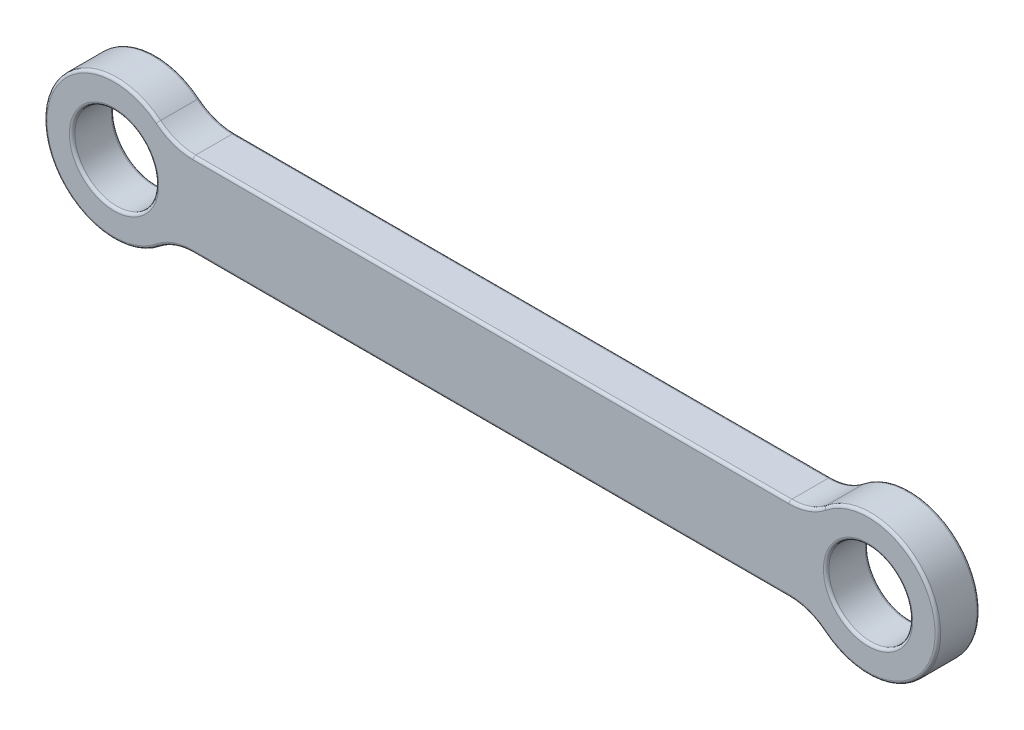
SolidWorks part; units mm, degrees
ref_plane "Front Plane" through (0, 0, 0) normal (0, 0, 1) x (1, 0, 0)
ref_plane "Top Plane" through (0, 0, 0) normal (0, 1, 0) x (1, 0, 0)
ref_plane "Right Plane" through (0, 0, 0) normal (1, 0, 0) x (0, 0, -1)
sketch "Sketch2" plane through (0, 0, 0) normal (0, 0, 1) x (1, 0, 0)
  line L0 (0, 0) -> (54, 0) construction
  line L1 (0, 5) -> (54, 5) construction
  line L2 (0, -5) -> (54, -5) construction
  line L3 (27, 0) -> (27, -5) construction
  line L5 (50, -3) -> (4, -3)
  line L6 (50, -3) -> (50, 3) construction
  line L7 (50, 3) -> (4, 3)
  line L8 (4, -3) -> (4, 3) construction
  line L9 (50, -3) -> (4, 3) construction
  line L10 (50, 3) -> (4, -3) construction
  arc A0 (0, 5) -> (0, -5) centre (0, 0) ccw construction
  arc A1 (54, -5) -> (54, 5) centre (54, 0) ccw construction
  circle A2 centre (0, 0) radius 5
  circle A4 centre (54, 0) radius 3
  circle A5 centre (54, 0) radius 5
  circle A6 centre (0, 0) radius 3
  point P3 (27, 0)
  dimension "D3" = 6
  dimension "D4" = 6
  dimension "D5" = 6
  dimension "D1" = 54
  dimension "D2" = 10
extrude "Boss-Extrude1" add sketch "Sketch2" along normal blind 3 contours A2 A6 | L5 A5 L7 A2 | A5 A4
fillet "Fillet1" radius 4 4 edges at (50, -3, 1.5) (4, -3, 1.5) (50, 3, 1.5) (4, 3, 1.5)
fillet "Fillet2" radius 0.2 20 edges at (57, 0, 0) (4.3235, -3.2288, 0) (27, -3, 0) (49.6765, -3.2288, 0) (59, 0, 0) (49.6765, 3.2288, 0) (27, 3, 0) (4.3235, 3.2288, 0) (-5, 0, 0) (3, 0, 0) (57, 0, 3) (49.6765, 3.2288, 3) (59, 0, 3) (49.6765, -3.2288, 3) (27, -3, 3) (4.3235, -3.2288, 3) (-5, 0, 3) (4.3235, 3.2288, 3) (27, 3, 3) (3, 0, 3)
